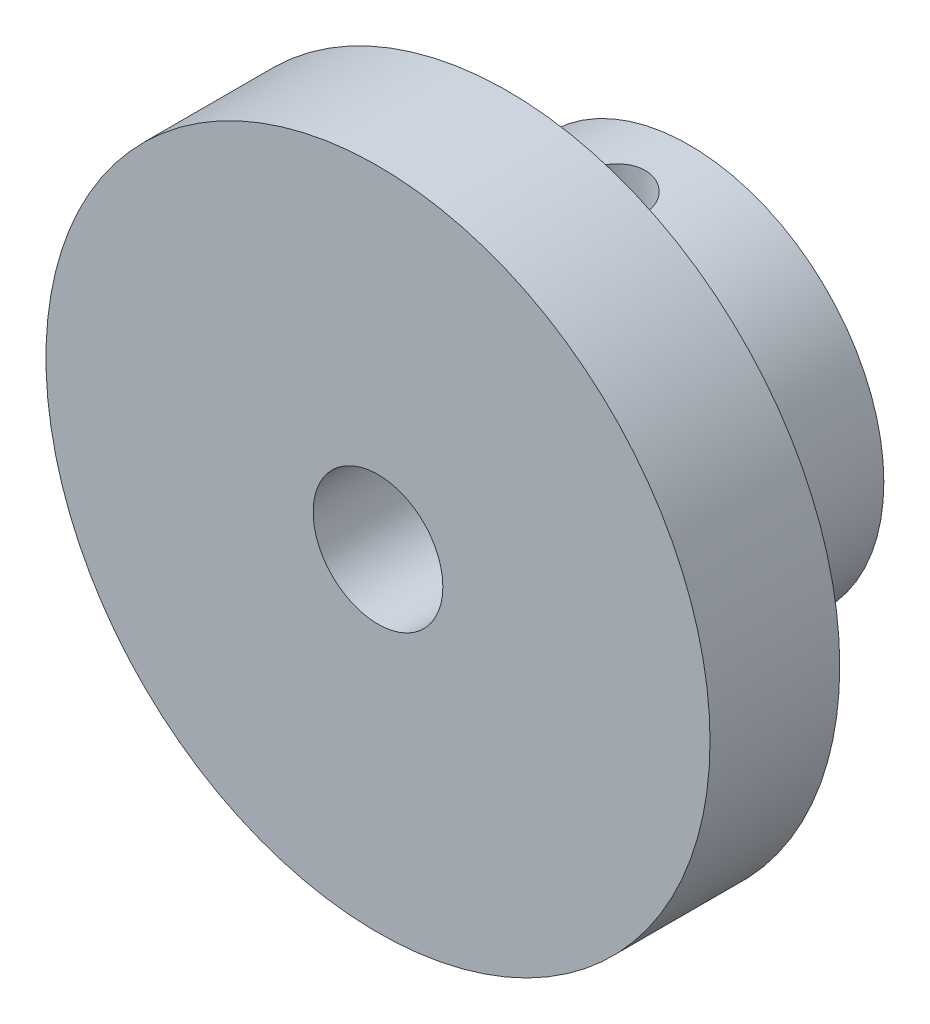
SolidWorks part; units mm, degrees
ref_plane "Front Plane" through (0, 0, 0) normal (0, 0, 1) x (1, 0, 0)
ref_plane "Top Plane" through (0, 0, 0) normal (0, 1, 0) x (1, 0, 0)
ref_plane "Right Plane" through (0, 0, 0) normal (1, 0, 0) x (0, 0, -1)
sketch "Sketch1" plane through (0, 0, 0) normal (0, 0, 1) x (1, 0, 0)
  circle A0 centre (0, 0) radius 7.5
extrude "Boss-Extrude1" add sketch "Sketch1" along normal blind 7
sketch "Sketch2" plane through (0, 0, 7) normal (0, 0, 1) x (1, 0, 0)
  circle A0 centre (0, 0) radius 12.8
extrude "Boss-Extrude2" add sketch "Sketch2" along normal blind 5
sketch "Sketch3" plane through (0, 0, 12) normal (0, 0, 1) x (1, 0, 0)
  circle A0 centre (0, 0) radius 2.5
extrude "Cut-Extrude1" cut sketch "Sketch3" against normal through all
hole_wizard "Tap Drill for M3x0.5 Tap1" positions "3DSketch1" profile "Sketch4" hole size "M3x0.5" standard "JIS"
sketch3d "3DSketch1"
  point P0 (0, 7.5, 3)
  point P1 (0, 0, 0)
sketch "Sketch4" plane through (0, 7.5, 3) normal (1, 0, 0) x (0, 0, 1)
  line L0 (0, 0) -> (0, 5)
  line L1 (0, 5) -> (1.3, 5)
  line L2 (1.3, 5) -> (1.3, 0)
  line L5 (1.3, 0) -> (0, 0)
  line L11 (0, -6.35) -> (0, 107.95) construction
  dimension "Thru Hole Dia." = 2.6
  dimension "Thru Hole Depth" = 5
